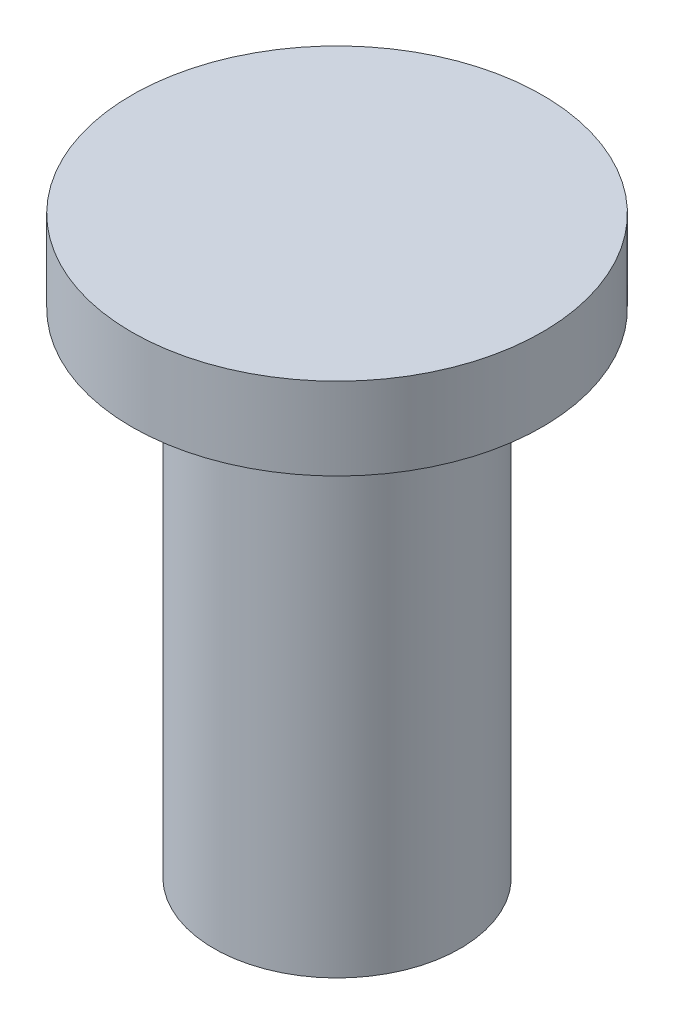
SolidWorks part; units mm, degrees
material "AISI 304"
ref_plane "前视基准面" through (0, 0, 0) normal (0, 0, 1) x (1, 0, 0)
ref_plane "上视基准面" through (0, 0, 0) normal (0, 1, 0) x (1, 0, 0)
ref_plane "右视基准面" through (0, 0, 0) normal (1, 0, 0) x (0, 0, -1)
other "Configuration Table"
sketch "草图1" plane through (0, 0, 0) normal (0, 1, 0) x (1, 0, 0)
  circle A0 centre (0, 0) radius 2.5
  dimension "D1" = 5
extrude "凸台-拉伸1" add sketch "草图1" along normal blind 1
sketch "草图2" plane through (0, 0, 0) normal (0, -1, 0) x (1, 0, 0)
  circle A0 centre (0, 0) radius 1.5
  dimension "D1" = 3
extrude "凸台-拉伸2" add sketch "草图2" along normal blind 6
